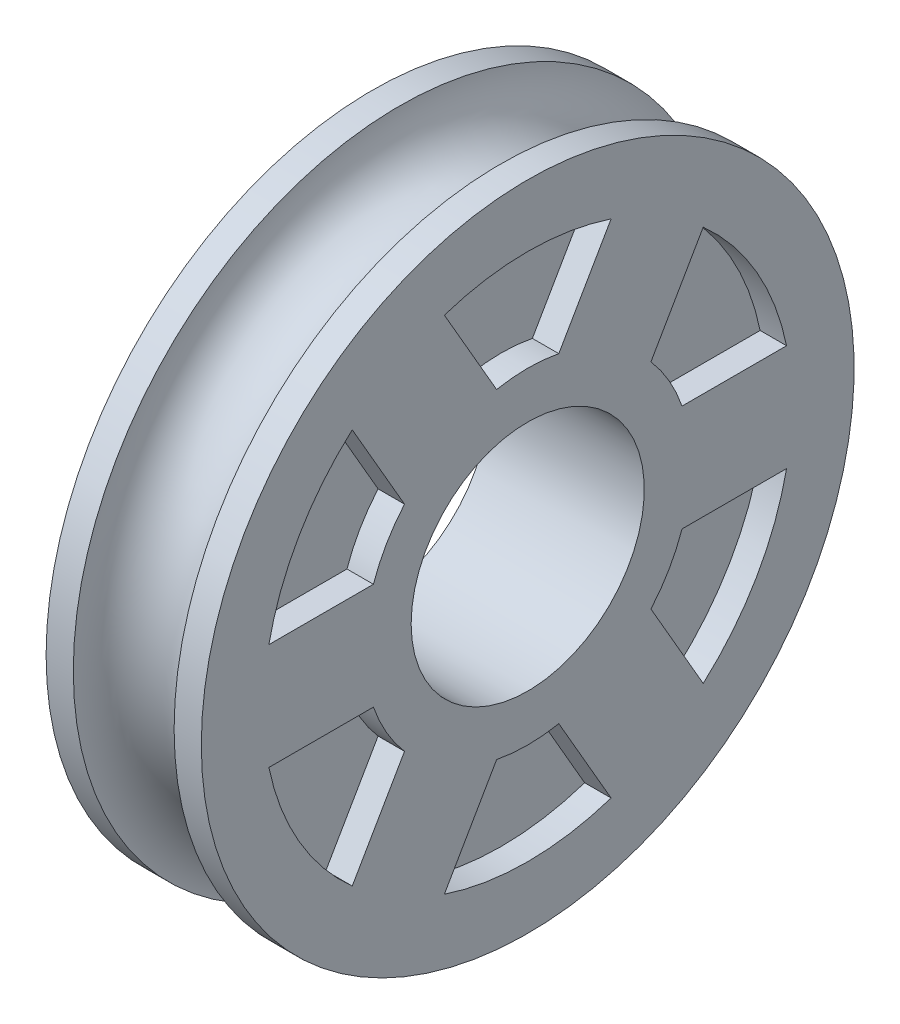
SolidWorks part; units mm, degrees
material "AISI 1035 Steel (SS)"
ref_plane "Front Plane" through (0, 0, 0) normal (0, 0, 1) x (1, 0, 0)
ref_plane "Top Plane" through (0, 0, 0) normal (0, 1, 0) x (1, 0, 0)
ref_plane "Right Plane" through (0, 0, 0) normal (1, 0, 0) x (0, 0, -1)
sketch "Sketch1" plane through (0, 0, 0) normal (0, 0, 1) x (1, 0, 0)
  line L0 (0, 0) -> (100, 0)
  line L1 (100, 0) -> (100, 210)
  line L2 (100, 210) -> (82.4997, 210)
  line L3 (0, 0) -> (0, 209.8556)
  line L4 (0, 209.8556) -> (17.5, 209.8556)
  arc A0 (17.5, 209.8556) -> (82.4997, 210) centre (50, 209.8556) ccw
  dimension "D4" = 65
  dimension "D1" = 210
  dimension "D2" = 100
  dimension "D3" = 17.5
  dimension "D5" = 17.5003
revolve "Revolve1" add sketch "Sketch1" angle 360 about L0
sketch "Sketch2" plane through (100, 0, 0) normal (1, 0, 0) x (0, 0, -1)
  circle A0 centre (0, 0) radius 75
  dimension "D1" = 150
extrude "Cut-Extrude1" cut sketch "Sketch2" against normal blind 258 and the other way blind 236
sketch "Sketch3" plane through (0, 0, 0) normal (-1, 0, 0) x (0, 0, 1)
  line L0 (20, 103.0776) -> (53.6264, 161.3202)
  line L1 (-53.6264, 161.3202) -> (-20, 103.0776)
  line L2 (0, 0) -> (254.1087, 0) construction
  line L3 (0, 0) -> (0, 251.6465) construction
  line L4 (112.8942, 127.1019) -> (79.2679, 68.8593)
  line L5 (99.2679, 34.2183) -> (166.5206, 34.2183)
  line L6 (166.5206, -34.2183) -> (99.2679, -34.2183)
  line L7 (79.2679, -68.8593) -> (112.8942, -127.1019)
  line L8 (53.6264, -161.3202) -> (20, -103.0776)
  line L9 (-20, -103.0776) -> (-53.6264, -161.3202)
  line L10 (-112.8942, -127.1019) -> (-79.2679, -68.8593)
  line L11 (-99.2679, -34.2183) -> (-166.5206, -34.2183)
  line L12 (-166.5206, 34.2183) -> (-99.2679, 34.2183)
  line L13 (-79.2679, 68.8593) -> (-112.8942, 127.1019)
  arc A0 (-79.2679, 68.8593) -> (-99.2679, 34.2183) centre (0, 0) ccw
  arc A1 (-112.8942, 127.1019) -> (-166.5206, 34.2183) centre (0, 0) ccw
  arc A2 (-99.2679, -34.2183) -> (-79.2679, -68.8593) centre (0, 0) ccw
  arc A3 (-166.5206, -34.2183) -> (-112.8942, -127.1019) centre (0, 0) ccw
  arc A4 (-53.6264, -161.3202) -> (53.6264, -161.3202) centre (0, 0) ccw
  arc A5 (-20, -103.0776) -> (20, -103.0776) centre (0, 0) ccw
  arc A6 (79.2679, -68.8593) -> (99.2679, -34.2183) centre (0, 0) ccw
  arc A7 (112.8942, -127.1019) -> (166.5206, -34.2183) centre (0, 0) ccw
  arc A8 (166.5206, 34.2183) -> (112.8942, 127.1019) centre (0, 0) ccw
  arc A9 (99.2679, 34.2183) -> (79.2679, 68.8593) centre (0, 0) ccw
  arc A10 (20, 103.0776) -> (-20, 103.0776) centre (0, 0) ccw
  arc A11 (53.6264, 161.3202) -> (-53.6264, 161.3202) centre (0, 0) ccw
  point P35 (0, 0)
  dimension "D1" = 210
  dimension "D2" = 340
  dimension "D3" = 60
  dimension "D4" = 60
  dimension "D5" = 20
  dimension "D6" = 20
  dimension "D7" = 6
extrude "Cut-Extrude2" cut sketch "Sketch3" against normal blind 17
ref_plane "Plane1" through (50, 0, 0) normal (1, 0, 0) x (0, 0, -1)
mirror "Mirror1" about plane through (50, 0, 0) normal (1, 0, 0) of "Cut-Extrude2"
